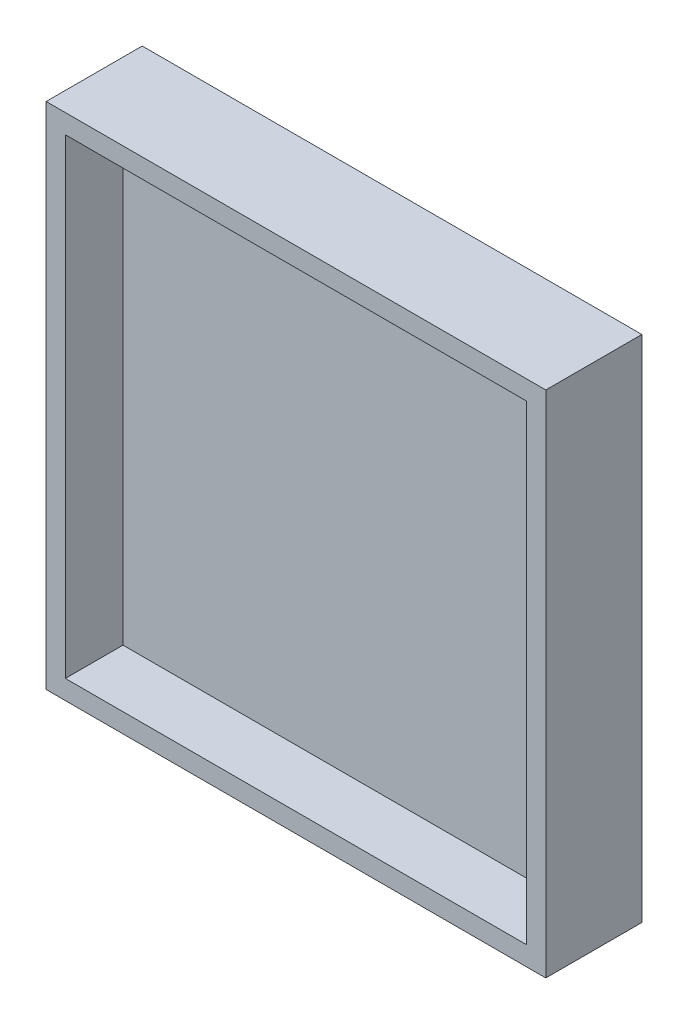
SolidWorks part; units mm, degrees
ref_plane "前视基准面" through (0, 0, 0) normal (0, 0, 1) x (1, 0, 0)
ref_plane "上视基准面" through (0, 0, 0) normal (0, 1, 0) x (1, 0, 0)
ref_plane "右视基准面" through (0, 0, 0) normal (1, 0, 0) x (0, 0, -1)
sketch "草图1" plane through (0, 0, 0) normal (0, 0, 1) x (1, 0, 0)
  line L1 (0, 0) -> (24, 0)
  line L2 (0, 0) -> (0, 24.5)
  line L3 (0, 24.5) -> (24, 24.5)
  line L4 (24, 0) -> (24, 24.5)
  line L5 (-1, -1) -> (25, -1)
  line L6 (-1, -1) -> (-1, 25.5)
  line L7 (-1, 25.5) -> (25, 25.5)
  line L8 (25, -1) -> (25, 25.5)
  dimension "D1" = 24
  dimension "D2" = 24.5
  dimension "D3" = 26
  dimension "D4" = 26.5
  dimension "D5" = 1
  dimension "D6" = 1
extrude "凸台-拉伸1" add sketch "草图1" along normal blind 3
sketch "草图2" plane through (0, 0, 0) normal (0, 0, -1) x (-1, 0, 0)
  line L1 (-25, 25.5) -> (1, 25.5)
  line L2 (-25, 25.5) -> (-25, -1)
  line L3 (-25, -1) -> (1, -1)
  line L4 (1, 25.5) -> (1, -1)
extrude "凸台-拉伸2" add sketch "草图2" along normal blind 2
